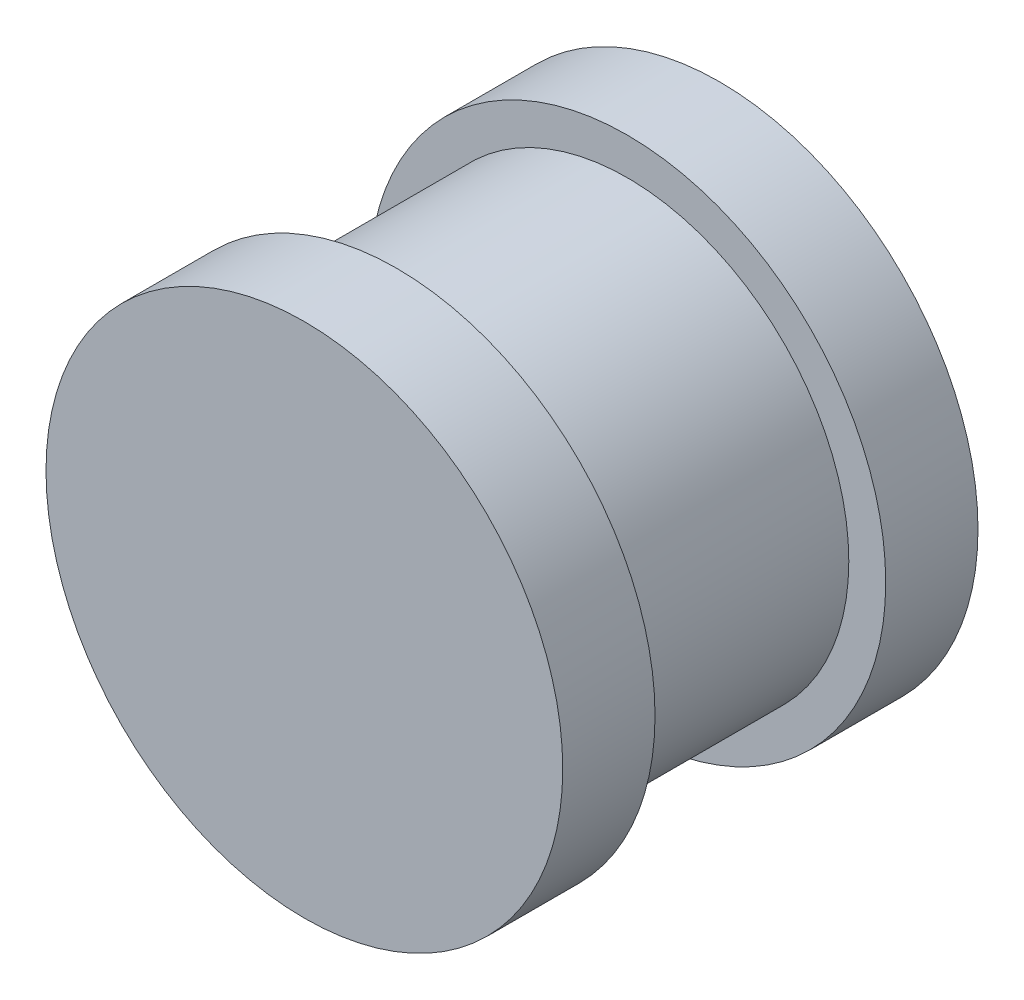
SolidWorks part; units mm, degrees
ref_plane "Front Plane" through (0, 0, 0) normal (0, 0, 1) x (1, 0, 0)
ref_plane "Top Plane" through (0, 0, 0) normal (0, 1, 0) x (1, 0, 0)
ref_plane "Right Plane" through (0, 0, 0) normal (1, 0, 0) x (0, 0, -1)
sketch "Sketch1" plane through (0, 0, 0) normal (0, 1, 0) x (1, 0, 0)
  line L0 (0, 0) -> (2.8, 0)
  line L1 (2.8, 0) -> (2.8, -1)
  line L2 (2.8, -1) -> (2.4, -1)
  line L3 (2.4, -1) -> (2.4, -3.5)
  line L4 (2.4, -3.5) -> (2.8, -3.5)
  line L5 (2.8, -3.5) -> (2.8, -4.5)
  line L6 (2.8, -4.5) -> (0, -4.5)
  line L7 (0, -4.5) -> (0, 0)
  point P3 (0, 0)
  dimension "D1" = 4.5
  dimension "D2" = 2.8
  dimension "D3" = 1
  dimension "D4" = 0.4
revolve "Revolve1" add sketch "Sketch1" angle 360 about L7
